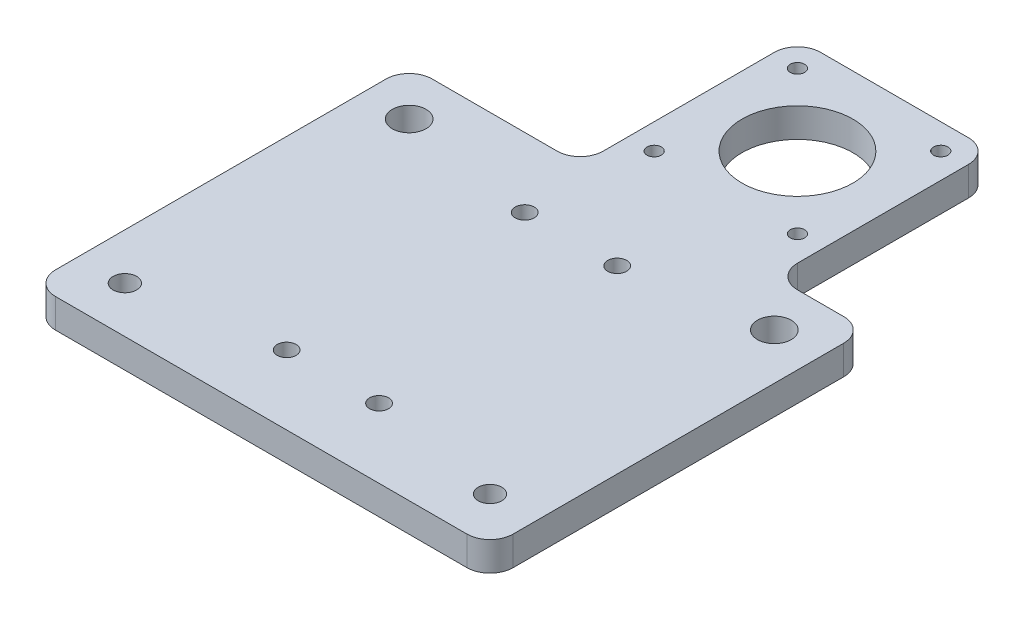
SolidWorks part; units mm, degrees
material "PET"
ref_plane "Front Plane" through (0, 0, 0) normal (0, 0, 1) x (1, 0, 0)
ref_plane "Top Plane" through (0, 0, 0) normal (0, 1, 0) x (1, 0, 0)
ref_plane "Right Plane" through (0, 0, 0) normal (1, 0, 0) x (0, 0, -1)
sketch "Sketch1" plane through (0, 0, 0) normal (0, 1, 0) x (1, 0, 0)
  line L0 (42.5, 123) -> (73.5, 123) construction
  line L1 (0, 0) -> (99, 0)
  line L2 (0, 0) -> (0, 81.5)
  line L3 (37, 128.5) -> (79, 128.5)
  line L4 (99, 0) -> (99, 81.5)
  line L5 (73.5, 123) -> (73.5, 92) construction
  line L6 (73.5, 92) -> (42.5, 92) construction
  line L7 (42.5, 92) -> (42.5, 123) construction
  line L8 (42.5, 123) -> (73.5, 92) construction
  line L9 (79, 81.5) -> (79, 128.5)
  line L12 (37, 81.5) -> (37, 128.5)
  line L13 (37, 81.5) -> (0, 81.5)
  line L14 (79, 81.5) -> (99, 81.5)
  line L15 (10, 71.5) -> (89, 71.5) construction
  line L16 (89, 71.5) -> (89, 10) construction
  line L17 (89, 10) -> (10, 10) construction
  line L18 (10, 10) -> (10, 71.5) construction
  line L19 (40, 66.5) -> (60, 66.5) construction
  line L20 (60, 66.5) -> (60, 15) construction
  line L21 (60, 15) -> (40, 15) construction
  line L22 (40, 15) -> (40, 66.5) construction
  circle A0 centre (58, 107.5) radius 12
  circle A1 centre (42.5, 123) radius 1.55
  circle A2 centre (73.5, 123) radius 1.55
  circle A3 centre (73.5, 92) radius 1.55
  circle A4 centre (42.5, 92) radius 1.55
  circle A5 centre (10, 71.5) radius 3.65
  circle A6 centre (89, 71.5) radius 3.65
  circle A7 centre (89, 10) radius 2.55
  circle A8 centre (10, 10) radius 2.55
  circle A9 centre (40, 66.5) radius 2.05
  circle A10 centre (60, 66.5) radius 2.05
  circle A11 centre (60, 15) radius 2.05
  circle A12 centre (40, 15) radius 2.05
  dimension "D3" = 31
  dimension "D2" = 3.1
  dimension "D7" = 3.1
  dimension "D8" = 3.1
  dimension "D9" = 3.1
  dimension "D16" = 5.1
  dimension "D17" = 5.1
  dimension "D18" = 7.3
  dimension "D19" = 7.3
  dimension "D24" = 4.1
  dimension "D25" = 4.1
  dimension "D26" = 4.1
  dimension "D27" = 4.1
  dimension "D1" = 99
  dimension "D4" = 58
  dimension "D5" = 42
  dimension "D6" = 47
  dimension "D10" = 21
  dimension "D11" = 21
  dimension "D12" = 10
  dimension "D13" = 10
  dimension "D14" = 10
  dimension "D15" = 10
  dimension "D20" = 51.5
  dimension "D21" = 20
  dimension "D22" = 15
  dimension "D23" = 40
extrude "Boss-Extrude1" add sketch "Sketch1" along normal blind 6.3
fillet "Fillet1" radius 5 8 edges at (0, 3.15, 0) (99, 3.15, 0) (99, 3.15, -81.5) (79, 3.15, -81.5) (79, 3.15, -128.5) (37, 3.15, -128.5) (37, 3.15, -81.5) (0, 3.15, -81.5)
